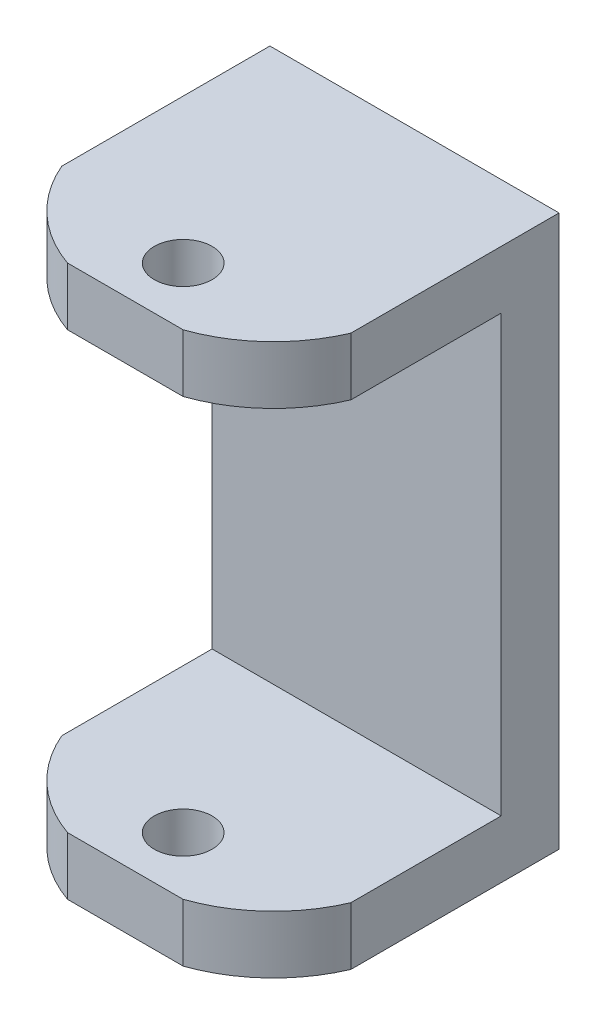
SolidWorks part; units mm, degrees
ref_plane "Front Plane" through (0, 0, 0) normal (0, 0, 1) x (1, 0, 0)
ref_plane "Top Plane" through (0, 0, 0) normal (0, 1, 0) x (1, 0, 0)
ref_plane "Right Plane" through (0, 0, 0) normal (1, 0, 0) x (0, 0, -1)
sketch "Sketch1" plane through (0, 0, 0) normal (0, 1, 0) x (1, 0, 0)
  line L1 (-5, 0) -> (5, 0)
  line L2 (-12.5, 7) -> (-12.5, 25)
  line L3 (-12.5, 25) -> (12.5, 25)
  line L4 (12.5, 7) -> (12.5, 25)
  arc A0 (5, 0) -> (12.5, 7) centre (0.8167, 12) ccw
  arc A1 (-5, 0) -> (-12.5, 7) centre (-0.8167, 12) cw
  circle A3 centre (0, 5) radius 2.5
  point P5 (0, 0)
  point P12 (-12.5, 0)
  point P13 (0, 25)
  dimension "D3" = 10
  dimension "D4" = 20
  dimension "D6" = 5
  dimension "D1" = 25
  dimension "D2" = 25
  dimension "D5" = 13
  dimension "D7" = 7
extrude "Boss-Extrude1" add sketch "Sketch1" along normal blind 47.65
sketch "Sketch2" plane through (-12.5, 0, 0) normal (-1, 0, 0) x (0, 0, 1)
  line L0 (0, 47.65) -> (0, 0) construction
  line L1 (0, 5) -> (-20, 5)
  line L2 (0, 5) -> (0, 42.65)
  line L3 (0, 42.65) -> (-20, 42.65)
  line L4 (-20, 5) -> (-20, 42.65)
  point P6 (0, 23.825)
  point P7 (0, 23.825)
  dimension "D1" = 37.65
  dimension "D2" = 20
extrude "Cut-Extrude1" cut sketch "Sketch2" against normal through all
ref_plane "B mid plane" through (0, 23.825, 0) normal (0, -1, 0) x (-1, 0, 0)
